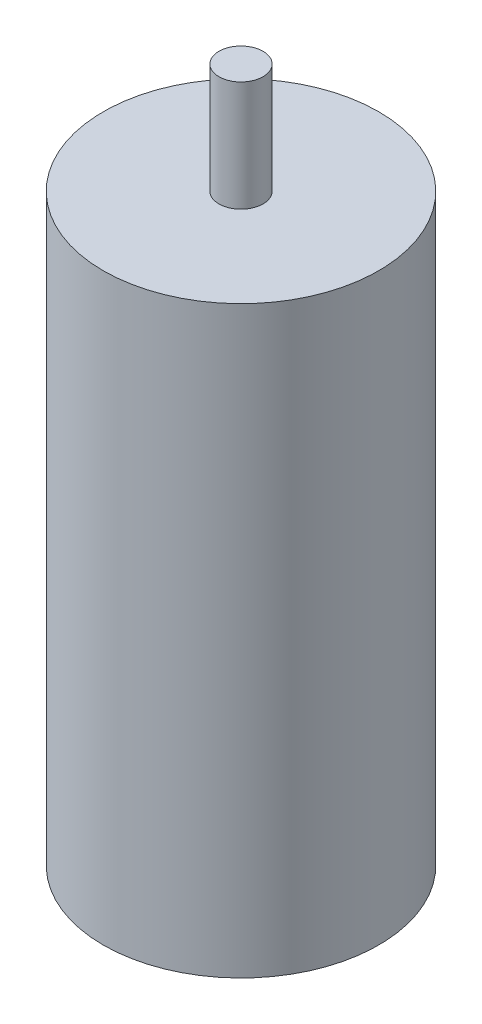
SolidWorks part; units mm, degrees
material "ABS"
ref_plane "Front Plane" through (0, 0, 0) normal (0, 0, 1) x (1, 0, 0)
ref_plane "Top Plane" through (0, 0, 0) normal (0, 1, 0) x (1, 0, 0)
ref_plane "Right Plane" through (0, 0, 0) normal (1, 0, 0) x (0, 0, -1)
sketch "Sketch1" plane through (0, 0, 0) normal (0, 1, 0) x (1, 0, 0)
  circle A0 centre (0, 0) radius 12.5
  dimension "D1" = 25
extrude "Boss-Extrude1" add sketch "Sketch1" along normal blind 53
sketch "Sketch2" plane through (0, 53, 0) normal (0, 1, 0) x (1, 0, 0)
  circle A0 centre (0, 0) radius 2
  dimension "D1" = 4
extrude "Boss-Extrude2" add sketch "Sketch2" along normal blind 10
